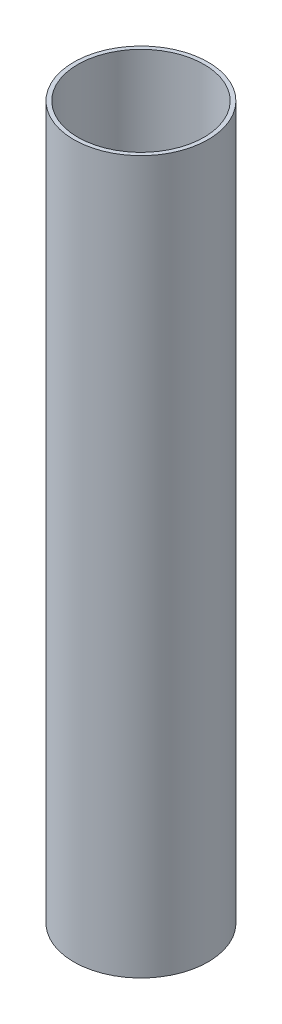
SolidWorks part; units mm, degrees
ref_plane "Front Plane" through (0, 0, 0) normal (0, 0, 1) x (1, 0, 0)
ref_plane "Top Plane" through (0, 0, 0) normal (0, 1, 0) x (1, 0, 0)
ref_plane "Right Plane" through (0, 0, 0) normal (1, 0, 0) x (0, 0, -1)
sketch "Sketch1" plane through (0, 0, 0) normal (0, 1, 0) x (1, 0, 0)
  circle A0 centre (0, 0) radius 19.5
  circle A1 centre (0, 0) radius 20.75
  dimension "D1" = 39
  dimension "D2" = 41.5
extrude "Boss-Extrude1" add sketch "Sketch1" along normal blind 220
